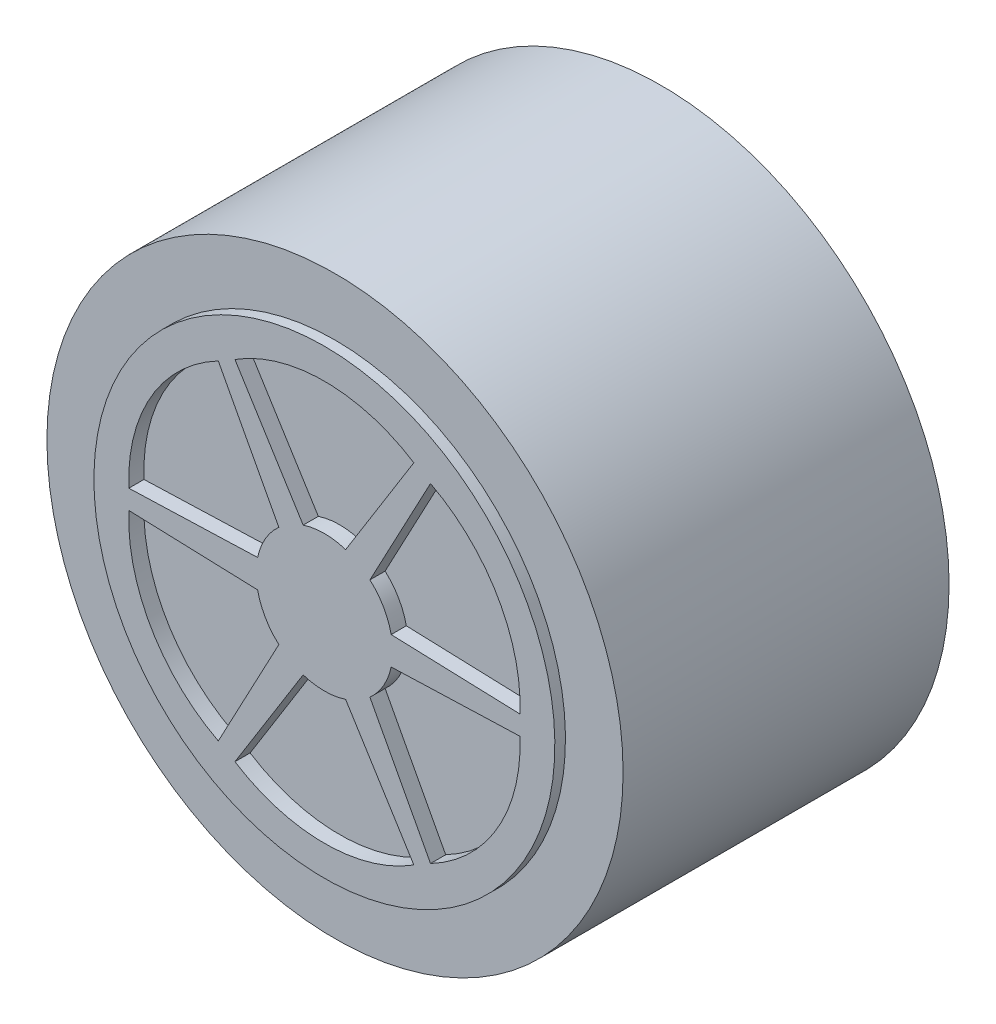
SolidWorks part; units mm, degrees
ref_plane "Alzado" through (0, 0, 0) normal (0, 0, 1) x (1, 0, 0)
ref_plane "Planta" through (0, 0, 0) normal (0, 1, 0) x (1, 0, 0)
ref_plane "Vista lateral" through (0, 0, 0) normal (1, 0, 0) x (0, 0, -1)
sketch "Croquis1" plane through (0, 0, 0) normal (1, 0, 0) x (0, 0, -1)
  line L0 (0, 0) -> (6.15, 0)
  line L1 (0, 0) -> (-16.05, 0)
  line L2 (-16.05, 0) -> (-16.05, 15.2)
  line L3 (-16.05, 15.2) -> (-15.35, 15.2)
  line L4 (-15.35, 15.2) -> (-15.35, 14.5)
  line L5 (-15.35, 14.5) -> (6.15, 14.5)
  line L15 (6.15, 14.5) -> (6.15, 0)
  dimension "D1" = 14.5
  dimension "D2" = 15.2
  dimension "D3" = 0.7
  dimension "D4" = 21.5
  dimension "D8" = 16.05
revolve "Revolución1" add sketch "Croquis1" angle 360 about L1
ref_plane "Plano1" through (0, 0, 12.95) normal (0, 0, 1) x (1, 0, 0)
sketch "Croquis5" plane through (0, 0, 16.05) normal (0, 0, 1) x (1, 0, 0)
  line L0 (0, 0) -> (0, 9.0083) construction
  line L1 (1.4, 4.2767) -> (5.9, 11.4878)
  line L2 (-1.4, 4.2767) -> (-5.9, 11.4878)
  line L3 (0, 13.2) -> (0, 15.2) construction
  line L4 (4.4037, 0.9259) -> (12.8987, 0.6343)
  line L5 (3.0037, 3.3508) -> (6.9987, 10.8534)
  line L6 (3.0037, -3.3508) -> (6.9987, -10.8534)
  line L7 (4.4037, -0.9259) -> (12.8987, -0.6343)
  line L8 (-1.4, -4.2767) -> (-5.9, -11.4878)
  line L9 (1.4, -4.2767) -> (5.9, -11.4878)
  line L10 (-4.4037, -0.9259) -> (-12.8987, -0.6343)
  line L11 (-3.0037, -3.3508) -> (-6.9987, -10.8534)
  line L12 (-3.0037, 3.3508) -> (-6.9987, 10.8534)
  line L13 (-4.4037, 0.9259) -> (-12.8987, 0.6343)
  circle A0 centre (0, 0) radius 4.5
  circle A1 centre (0, 0) radius 15.2 construction
  arc A2 (6.9987, 10.8534) -> (12.8987, 0.6343) centre (1.8868, 1.0894) cw
  arc A3 (-5.9, 11.4878) -> (5.9, 11.4878) centre (0, 2.1787) cw
  arc A4 (12.8987, -0.6343) -> (6.9987, -10.8534) centre (1.8868, -1.0894) cw
  arc A5 (5.9, -11.4878) -> (-5.9, -11.4878) centre (0, -2.1787) cw
  arc A6 (-6.9987, -10.8534) -> (-12.8987, -0.6343) centre (-1.8868, -1.0894) cw
  arc A7 (-12.8987, 0.6343) -> (-6.9987, 10.8534) centre (-1.8868, 1.0894) cw
  point P41 (0, 0)
  dimension "D1" = 9
  dimension "D3" = 2
  dimension "D2" = 1.4
  dimension "D5" = 4.5
  dimension "D6" = 8.5
  dimension "D4" = 6
extrude "Cortar-Extruir4" cut sketch "Croquis5" against normal blind 1 contours A3 L2 A0 L1 | A2 L5 A0 L4 | A4 L7 A0 L6 | A5 L9 A0 L8 | A6 L11 A0 L10 | A7 L13 A0 L12
sketch "Croquis7" plane through (0, 0, -6.15) normal (0, 0, -1) x (-1, 0, 0)
  circle A0 centre (0, 0) radius 7.5
  dimension "D1" = 15
extrude "Cortar-Extruir5" cut sketch "Croquis7" against normal blind 9
sketch "Croquis8" plane through (0, 0, 2.85) normal (0, 0, -1) x (-1, 0, 0)
  line L0 (-1.1402, -1.05) -> (1.1402, -1.05)
  arc A0 (1.1402, -1.05) -> (-1.1402, -1.05) centre (0, 0) ccw
  dimension "D1" = 3.1
  dimension "D2" = 1.05
extrude "Cortar-Extruir6" cut sketch "Croquis8" against normal blind 9
ref_plane "Plano2" through (0, -11.25, 0) normal (0, 1, 0) x (1, 0, 0)
sketch "Croquis10" plane through (0, -11.25, 0) normal (0, 1, 0) x (1, 0, 0)
  line L0 (15.2, -15.35) -> (-15.2, -15.35) construction
  circle A0 centre (0, -8.85) radius 3
  dimension "D2" = 6
  dimension "D1" = 6.5
extrude "Cortar-Extruir8" cut sketch "Croquis10" along normal blind 5 and the other way through all
sketch "Croquis11" plane through (0, -6.25, 0) normal (0, -1, 0) x (1, 0, 0)
  circle A0 centre (0, 8.85) radius 1.5
  dimension "D1" = 3
extrude "Cortar-Extruir9" cut sketch "Croquis11" against normal up to surface (5.2 mm away) up to face at (0, -1.05, 7.35)
sketch "Croquis12" plane through (0, 0, 0) normal (1, 0, 0) x (0, 0, -1)
  line L0 (-15.35, 14.5) -> (-15.35, 19)
  line L1 (-15.35, 19) -> (6.15, 19)
  line L2 (6.15, 19) -> (6.15, 14.5)
  line L3 (6.15, 14.5) -> (-15.35, 14.5)
  line L4 (-12.0431, 0) -> (16.908, 0) construction
  dimension "D1" = 4.5
revolve "Revolución2" add sketch "Croquis12" angle 360 about L4
